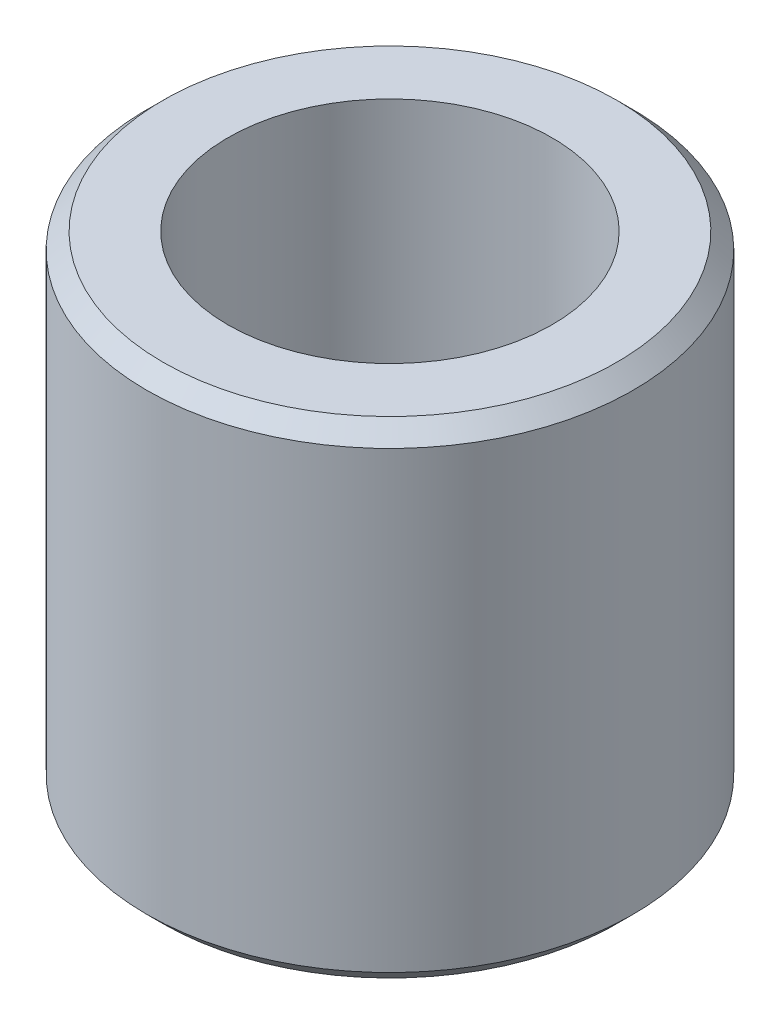
SolidWorks part; units mm, degrees
ref_plane "Front Plane" through (0, 0, 0) normal (0, 0, 1) x (1, 0, 0)
ref_plane "Top Plane" through (0, 0, 0) normal (0, 1, 0) x (1, 0, 0)
ref_plane "Right Plane" through (0, 0, 0) normal (1, 0, 0) x (0, 0, -1)
sketch "Sketch1" plane through (0, 0, 0) normal (0, 1, 0) x (1, 0, 0)
  circle A0 centre (0, 0) radius 254
  circle A1 centre (0, 0) radius 381
  dimension "D1" = 762
  dimension "D2" = 508
extrude "Boss-Extrude1" add sketch "Sketch1" along normal mid plane 762
chamfer "Chamfer1" distance 25.4 angle 45 2 edges at (0, -381, 381) (0, 381, 381)
